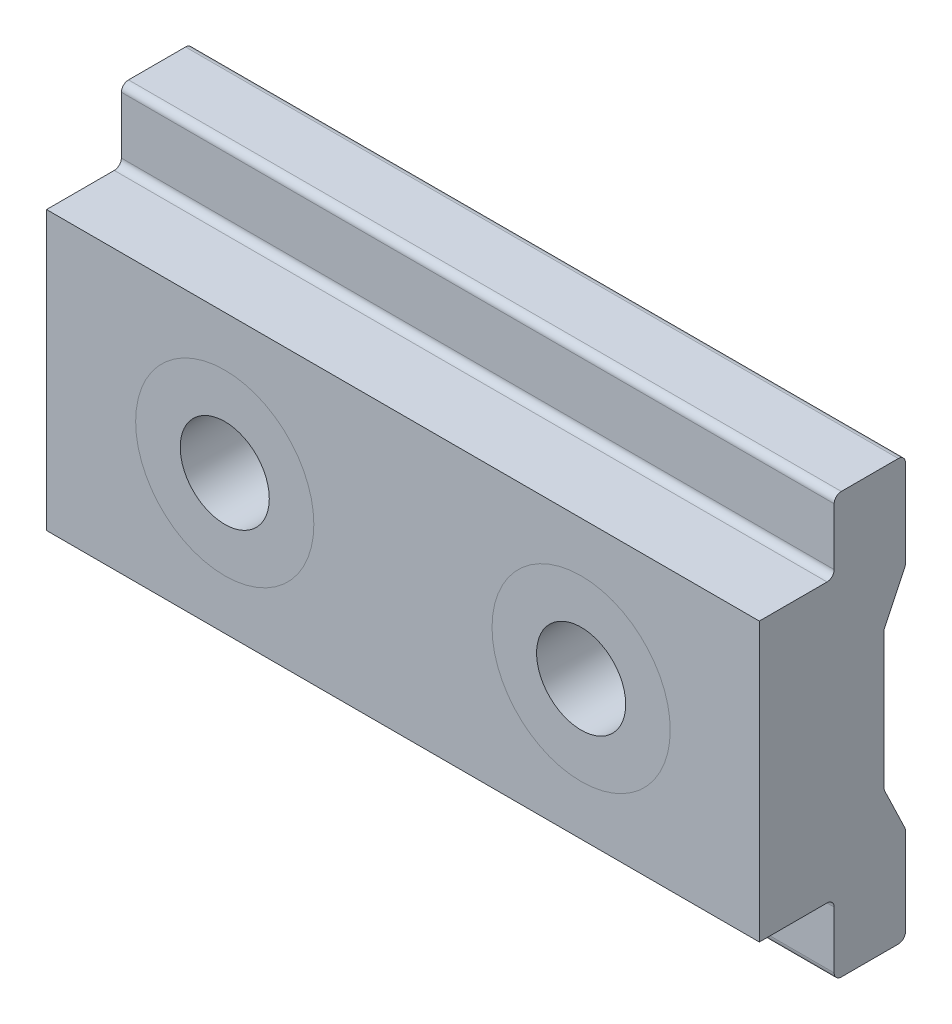
SolidWorks part; units mm, degrees
ref_plane "前视基准面" through (0, 0, 0) normal (0, 0, 1) x (1, 0, 0)
ref_plane "上视基准面" through (0, 0, 0) normal (0, 1, 0) x (1, 0, 0)
ref_plane "右视基准面" through (0, 0, 0) normal (1, 0, 0) x (0, 0, -1)
sketch "草图1" plane through (0, 0, 0) normal (1, 0, 0) x (0, 0, -1)
  line L0 (-5, 4.35) -> (-6, 4.35)
  line L1 (-6, 4.35) -> (-6, 7.5)
  line L2 (-6, 7.5) -> (0, 7.5)
  line L3 (0, 7.5) -> (0, -7.5)
  line L4 (-5, 4.35) -> (-5, 6)
  line L5 (-5, 6) -> (-2.8, 6)
  line L6 (-2.8, 6) -> (-2.8, -6)
  line L7 (55, 0) -> (-55, 0) construction
  line L8 (-5, -6) -> (-2.8, -6)
  line L9 (-5, -4.35) -> (-5, -6)
  line L10 (-6, -7.5) -> (0, -7.5)
  line L11 (-6, -4.35) -> (-6, -7.5)
  line L12 (-5, -4.35) -> (-6, -4.35)
  line L13 (-7, 3.9) -> (-7, -3.9)
  line L14 (-7, 3.9) -> (-4.9, 3.9)
  line L15 (-4.9, 3.9) -> (-4.9, 5.9)
  line L16 (-4.9, 5.9) -> (-2.9, 5.9)
  line L17 (-2.9, 5.9) -> (-2.9, 3.2)
  line L18 (-2.9, 3.2) -> (-3.5, 1.95)
  line L19 (-3.5, 1.95) -> (-3.5, -1.95)
  line L20 (-2.9, -3.2) -> (-3.5, -1.95)
  line L21 (-2.9, -5.9) -> (-2.9, -3.2)
  line L22 (-4.9, -5.9) -> (-2.9, -5.9)
  line L23 (-4.9, -3.9) -> (-4.9, -5.9)
  line L24 (-7, -3.9) -> (-4.9, -3.9)
  line L25 (-317.1337, 1113.4359) -> (-53.8004, 1113.4359) construction
  line L26 (23.8654, 1077.0309) -> (287.1987, 1077.0309) construction
  point P19 (-4.6783, -2.0661)
  point P21 (-3.3875, 3.2834)
  point P24 (-5.1252, 3.9)
  point P30 (-7, -3.7653)
  point P31 (-5.2967, 5.8084)
  point P34 (-4.8878, -3.9)
  point P37 (-3.5, -2.1351)
  point P38 (-3.5, -1.95)
  point P39 (-3.5, -1.95)
  point P40 (-3.5, 1.95)
  point P41 (-2.9, 3.5256)
  dimension "D1" = 15
  dimension "D2" = 6
  dimension "D3" = 2.8
  dimension "D4" = 8.7
  dimension "D5" = 7
  dimension "D6" = 7.8
  dimension "D7" = 3.5
  dimension "D8" = 4.1
  dimension "D9" = 11.8
  dimension "D10" = 0.1
  dimension "D11" = 1
  dimension "D13" = 3.9
  dimension "D14" = 2.7
  dimension "D15" = 0.1
extrude "凸台-拉伸1" add sketch "草图1" along normal mid plane 20 contours L13 L24 L23 L22 L21 L20 L19 L18 L17 L16 L15 L14
fillet "圆角1" radius 0.2 10 edges at (0, -3.2, 2.9) (0, 3.2, 2.9) (0, 5.9, 2.9) (0, -5.9, 2.9) (0, -5.9, 4.9) (0, -3.9, 4.9) (0, 3.9, 4.9) (0, 5.9, 4.9) (0, -1.95, 3.5) (0, 1.95, 3.5)
sketch "草图4" plane through (0, 0, 7) normal (0, 0, 1) x (1, 0, 0)
  line L0 (-5, 0) -> (5, 0) construction
  circle A0 centre (-5, 0) radius 2.5
  circle A1 centre (5, 0) radius 2.5
  dimension "D2" = 5
  dimension "D1" = 10
extrude "切除-拉伸1" cut sketch "草图4" against normal through all
sketch "草图5" plane through (0, 0, 7) normal (0, 0, 1) x (1, 0, 0)
  circle A0 centre (5, 0) radius 2.5 construction
  circle A1 centre (-5, 0) radius 2.5 construction
  circle A2 centre (5, 0) radius 2.5
  circle A3 centre (-5, 0) radius 2.5
extrude "凸台-拉伸2" add sketch "草图5" against normal up to surface (3.5 mm away) separate body up to face at (0, 0, 3.5)
hole_wizard "M3 螺纹孔1" positions "草图2" profile "草图3" tap size "M3" standard "GB" end condition through all
sketch "草图2" plane through (0, 0, 7) normal (0, 0, 1) x (1, 0, 0)
  point P0 (-5, 0)
  point P34 (5, 0)
sketch "草图3" plane through (-5, 0, 7) normal (1, 0, 0) x (0, -1, 0)
  line L0 (0, 0) -> (0, 4.1)
  line L1 (0, 4.1) -> (1.25, 4.1)
  line L2 (1.25, 4.1) -> (1.25, 0)
  line L5 (1.25, 0) -> (0, 0)
  line L11 (0, -6.35) -> (0, 107.95) construction
  dimension "通孔螺纹孔钻头直径" = 2.5
  dimension "通孔螺纹孔钻头深度" = 4.1
cosmetic thread "孔螺蚊线1" parameters "D2"=3
cosmetic thread "孔螺蚊线2" parameters "D2"=3
